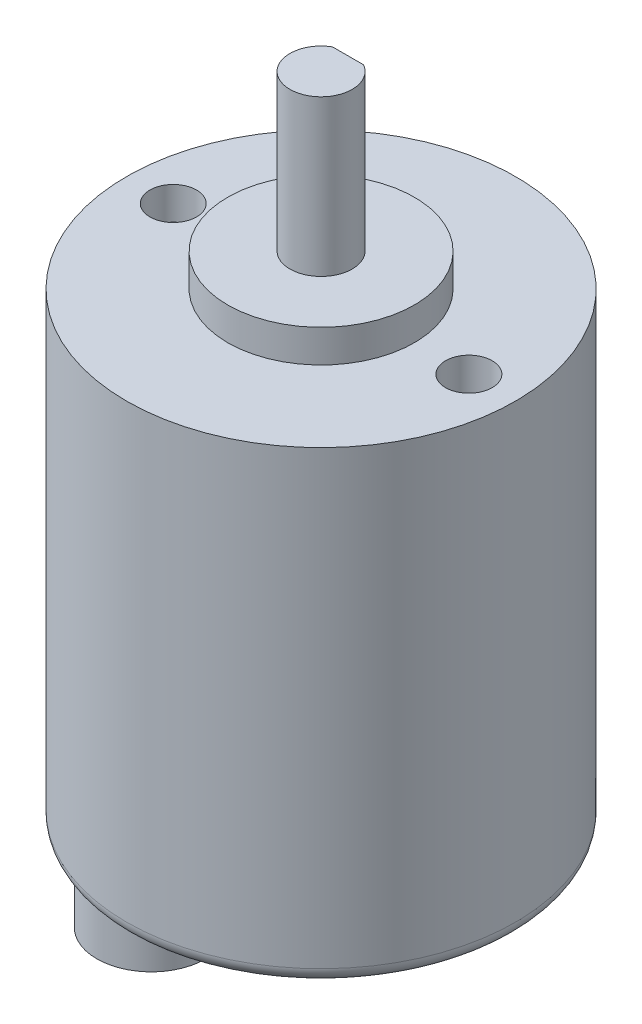
SolidWorks part; units mm, degrees
ref_plane "前视基准面" through (0, 0, 0) normal (0, 0, 1) x (1, 0, 0)
ref_plane "上视基准面" through (0, 0, 0) normal (0, 1, 0) x (1, 0, 0)
ref_plane "右视基准面" through (0, 0, 0) normal (1, 0, 0) x (0, 0, -1)
sketch "草图1" plane through (0, 0, 0) normal (0, 1, 0) x (1, 0, 0)
  circle A0 centre (0, 0) radius 12.5
  dimension "D1" = 25
extrude "凸台-拉伸1" add sketch "草图1" along normal blind 30
fillet "圆角1" radius 1 1 edges at (0, 0, 12.5)
sketch "草图2" plane through (0, 30, 0) normal (0, 1, 0) x (1, 0, 0)
  circle A0 centre (0, 0) radius 6
  dimension "D1" = 12
extrude "凸台-拉伸2" add sketch "草图2" along normal blind 2.1
sketch "草图3" plane through (0, 30, 0) normal (0, 1, 0) x (1, 0, 0)
  line L0 (-13.886, 0) -> (13.3346, 0) construction
  line L1 (0, -14.0865) -> (0, 13.3847) construction
  circle A0 centre (-9.5, 0) radius 1.5
  circle A1 centre (9.5, 0) radius 1.5
  dimension "D1" = 19
  dimension "D2" = 3
extrude "切除-拉伸1" cut sketch "草图3" against normal blind 2.1
sketch "草图4" plane through (0, 32.1, 0) normal (0, 1, 0) x (1, 0, 0)
  circle A0 centre (0, 0) radius 2
  dimension "D1" = 4
extrude "凸台-拉伸3" add sketch "草图4" along normal blind 10
sketch "草图5" plane through (0, 42.1, 0) normal (0, 1, 0) x (1, 0, 0)
  line L0 (-0.9973, 1.7336) -> (0.9973, 1.7336)
  circle A0 centre (0, 0) radius 2 construction
  arc A1 (-0.9973, 1.7336) -> (0.9973, 1.7336) centre (0, 0) cw
  circle M1 centre (0, 0) radius 2
extrude "切除-拉伸2" cut sketch "草图5" against normal blind 7 contours L0 M1
sketch "草图6" plane through (0, 0, 0) normal (0, -1, 0) x (1, 0, 0)
  circle A0 centre (-6.9137, 3.9967) radius 3.5
  dimension "D1" = 7
extrude "凸台-拉伸4" add sketch "草图6" along normal blind 7
